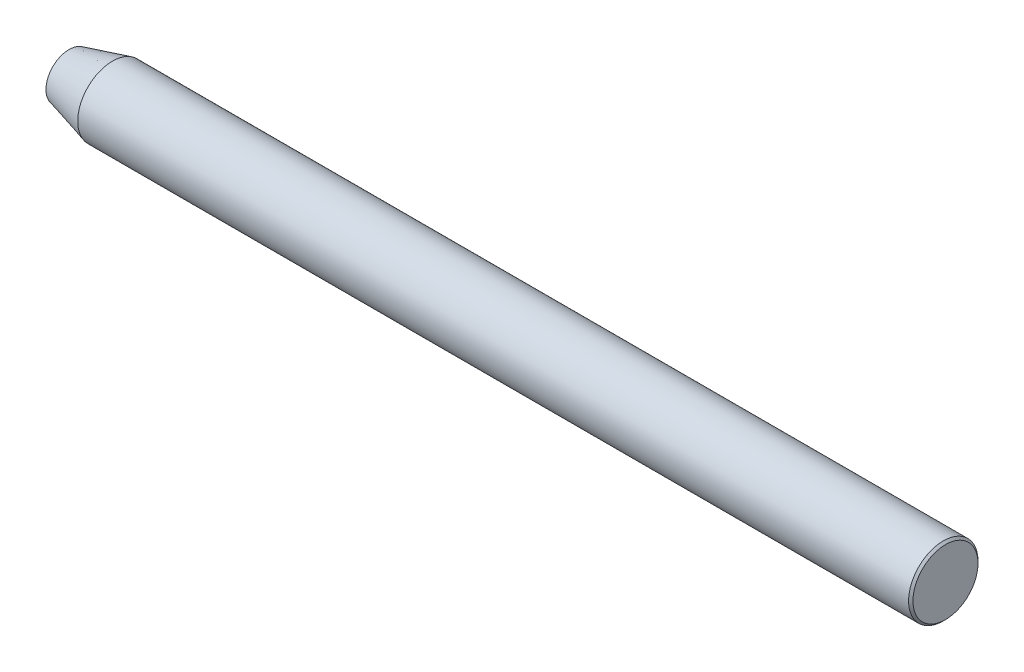
SolidWorks part; units mm, degrees
ref_plane "Front Plane" through (0, 0, 0) normal (0, 0, 1) x (1, 0, 0)
ref_plane "Top Plane" through (0, 0, 0) normal (0, 1, 0) x (1, 0, 0)
ref_plane "Right Plane" through (0, 0, 0) normal (1, 0, 0) x (0, 0, -1)
sketch "Sketch1" plane through (0, 0, 0) normal (0, 0, 1) x (1, 0, 0)
  line L0 (0, 5.3205) -> (0, 0)
  line L1 (0, 0) -> (202, 0)
  line L2 (202, 0) -> (202, 7.5)
  line L3 (202, 7.5) -> (201.5, 8)
  line L4 (201.5, 8) -> (10, 8)
  line L5 (10, 8) -> (0, 5.3205)
  line L6 (-0.005, 0) -> (202.005, 0) construction
revolve "Revolve1" add sketch "Sketch1" angle 360 about L6
